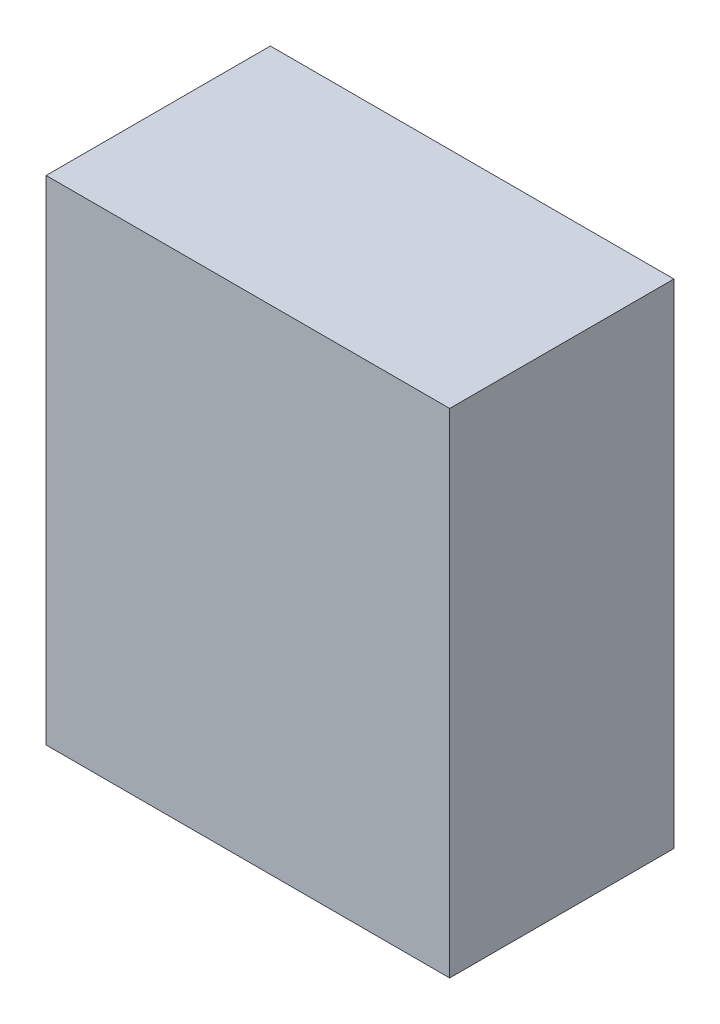
SolidWorks part; units mm, degrees
ref_plane "Front Plane" through (0, 0, 0) normal (0, 0, 1) x (1, 0, 0)
ref_plane "Top Plane" through (0, 0, 0) normal (0, 1, 0) x (1, 0, 0)
ref_plane "Right Plane" through (0, 0, 0) normal (1, 0, 0) x (0, 0, -1)
sketch "Sketch1" plane through (0, 0, 0) normal (0, 0, 1) x (1, 0, 0)
  line L0 (-18, 22) -> (18, -22) construction
  line L1 (-18, 22) -> (18, 22)
  line L2 (-18, 22) -> (-18, -22)
  line L3 (-18, -22) -> (18, -22)
  line L4 (18, 22) -> (18, -22)
  point P4 (-18, 19.2656)
  dimension "D1" = 36
  dimension "D2" = 44
extrude "Boss-Extrude1" add sketch "Sketch1" along normal blind 20
